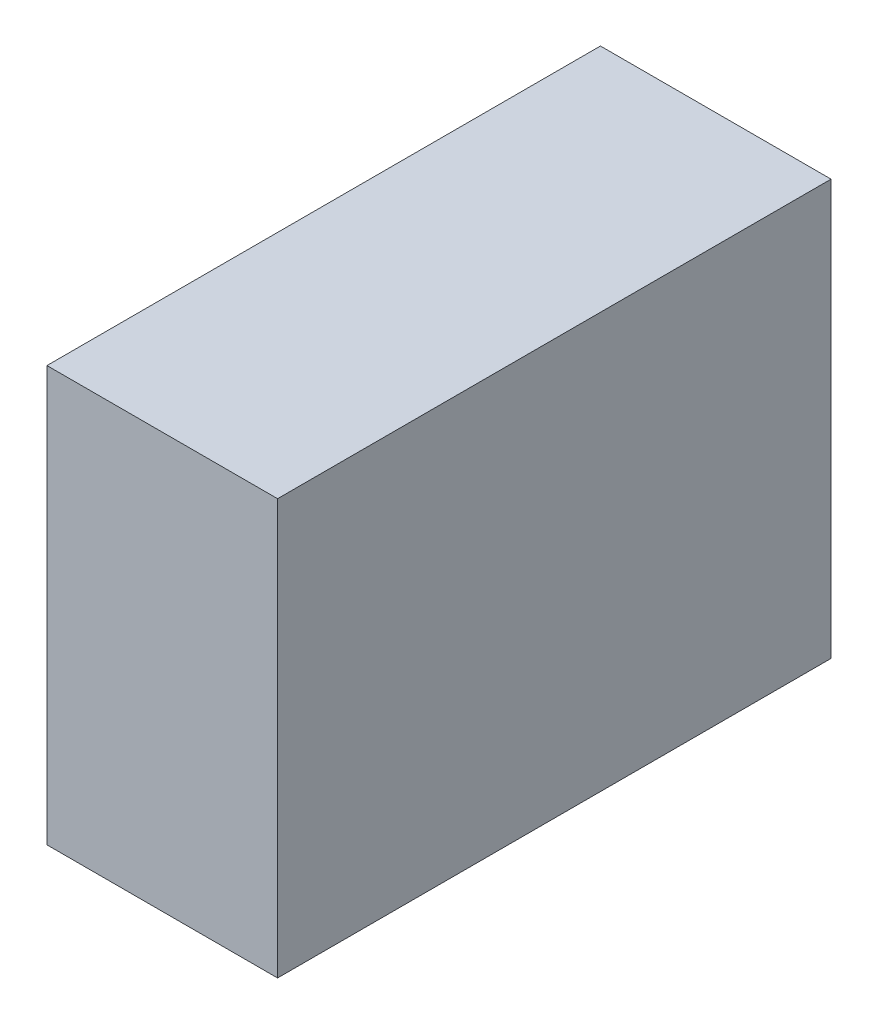
SolidWorks part; units mm, degrees
ref_plane "정면" through (0, 0, 0) normal (0, 0, 1) x (1, 0, 0)
ref_plane "윗면" through (0, 0, 0) normal (0, 1, 0) x (1, 0, 0)
ref_plane "우측면" through (0, 0, 0) normal (1, 0, 0) x (0, 0, -1)
sketch "스케치1" plane through (0, 0, 0) normal (0, 0, 1) x (1, 0, 0)
  line L1 (0, 0) -> (50, 0)
  line L2 (0, 0) -> (0, 90)
  line L3 (0, 90) -> (50, 90)
  line L4 (50, 0) -> (50, 90)
  dimension "D1" = 50
  dimension "D2" = 90
extrude "보스-돌출1" add sketch "스케치1" along normal blind 120
sketch "스케치2" plane through (0, 0, 0) normal (-1, 0, 0) x (0, 0, 1)
  line L0 (120, 90) -> (0, 90) construction
  line L1 (30, 90) -> (90, 90)
  line L2 (30, 90) -> (30, 30)
  line L3 (30, 30) -> (90, 30)
  line L4 (90, 90) -> (90, 30)
  line L5 (120, 90) -> (120, 0) construction
  line L6 (120, 0) -> (0, 0) construction
  dimension "D1" = 60
  dimension "D2" = 30
  dimension "D3" = 30
